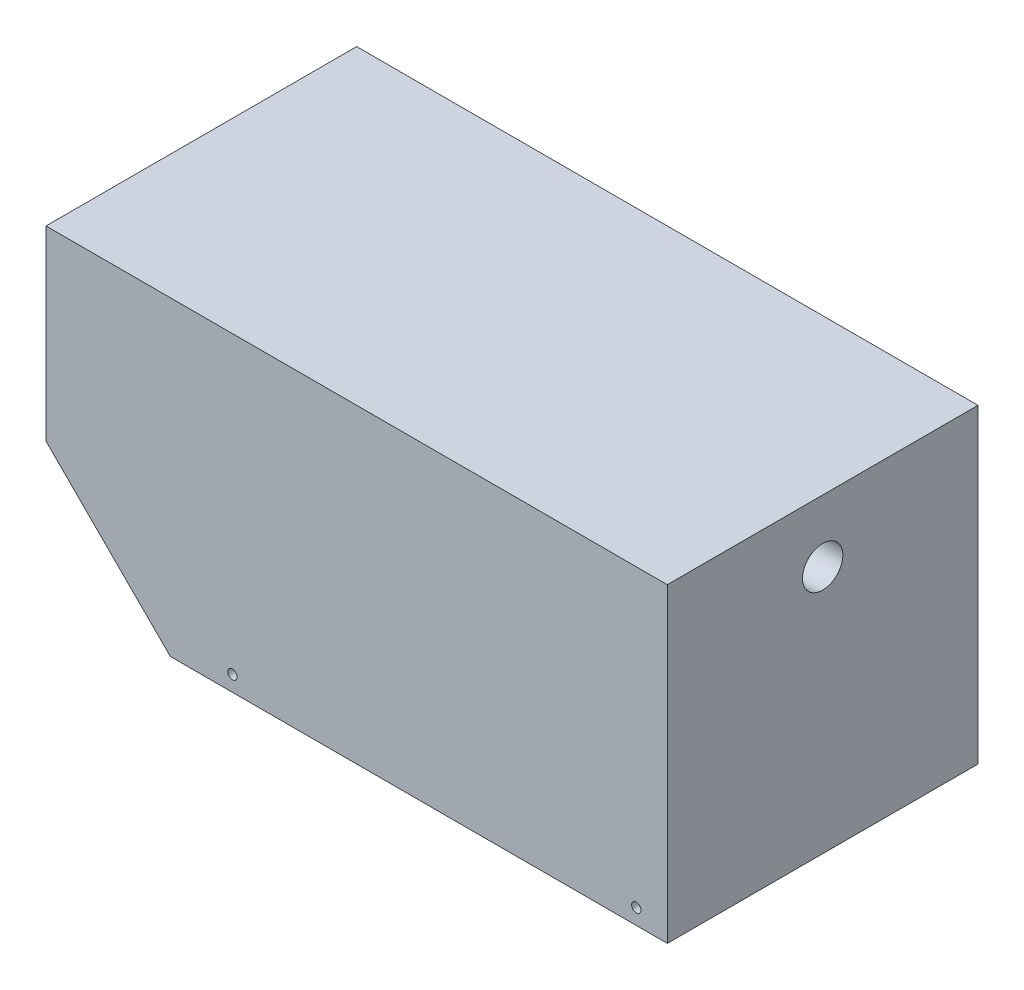
SolidWorks part; units mm, degrees
ref_plane "Plan de face" through (0, 0, 0) normal (0, 0, 1) x (1, 0, 0)
ref_plane "Plan de dessus" through (0, 0, 0) normal (0, 1, 0) x (1, 0, 0)
ref_plane "Plan de droite" through (0, 0, 0) normal (1, 0, 0) x (0, 0, -1)
sketch "Esquisse1" plane through (0, 0, 0) normal (0, 0, 1) x (1, 0, 0)
  line L1 (100, -50) -> (-100, -50)
  line L2 (100, -50) -> (100, 50)
  line L3 (100, 50) -> (-100, 50)
  line L4 (-100, -50) -> (-100, 50)
  line L5 (100, -50) -> (-100, 50) construction
  line L6 (100, 50) -> (-100, -50) construction
  point P0 (0, 0)
  dimension "D1" = 200
  dimension "D2" = 100
extrude "Boss.-Extru.1" add sketch "Esquisse1" along normal blind 100
chamfer "Chanfrein1" distance 40 angle 45 1 edges at (-100, -50, 50)
sketch "Esquisse2" plane through (100, 0, 0) normal (1, 0, 0) x (0, 0, -1)
  line L0 (-100, 50) -> (0, 50) construction
  line L1 (0, -50) -> (0, 50) construction
  circle A0 centre (-50, 30) radius 6.5
  dimension "D1" = 13
  dimension "D2" = 20
  dimension "D3" = 50
extrude "Enlèv. mat.-Extru.1" cut sketch "Esquisse2" against normal through all
sketch "Esquisse4" plane through (0, 0, 100) normal (0, 0, 1) x (1, 0, 0)
  line L0 (100, -50) -> (100, 50) construction
  line L1 (-60, -50) -> (100, -50) construction
  circle A0 centre (90, -45) radius 1.5
  circle A1 centre (-40, -45) radius 1.5
  point P4 (0, 0)
  dimension "D1" = 3
  dimension "D2" = 10
  dimension "D3" = 5
  dimension "D4" = 140
extrude "Enlèv. mat.-Extru.3" cut sketch "Esquisse4" against normal through all
sketch "Esquisse5" plane through (0, -50, 0) normal (0, -1, 0) x (1, 0, 0)
  line L0 (-60, 0) -> (100, 0) construction
  line L1 (96, 4) -> (-56, 4)
  line L2 (96, 4) -> (96, 96)
  line L3 (96, 96) -> (-56, 96)
  line L4 (-56, 4) -> (-56, 96)
  line L5 (-60, 100) -> (100, 100) construction
  line L6 (100, 100) -> (100, 0) construction
  line L7 (-60, 100) -> (-60, 0) construction
  dimension "D1" = 4
  dimension "D2" = 4
  dimension "D3" = 4
  dimension "D4" = 4
extrude "Enlèv. mat.-Extru.4" cut sketch "Esquisse5" against normal blind 70
